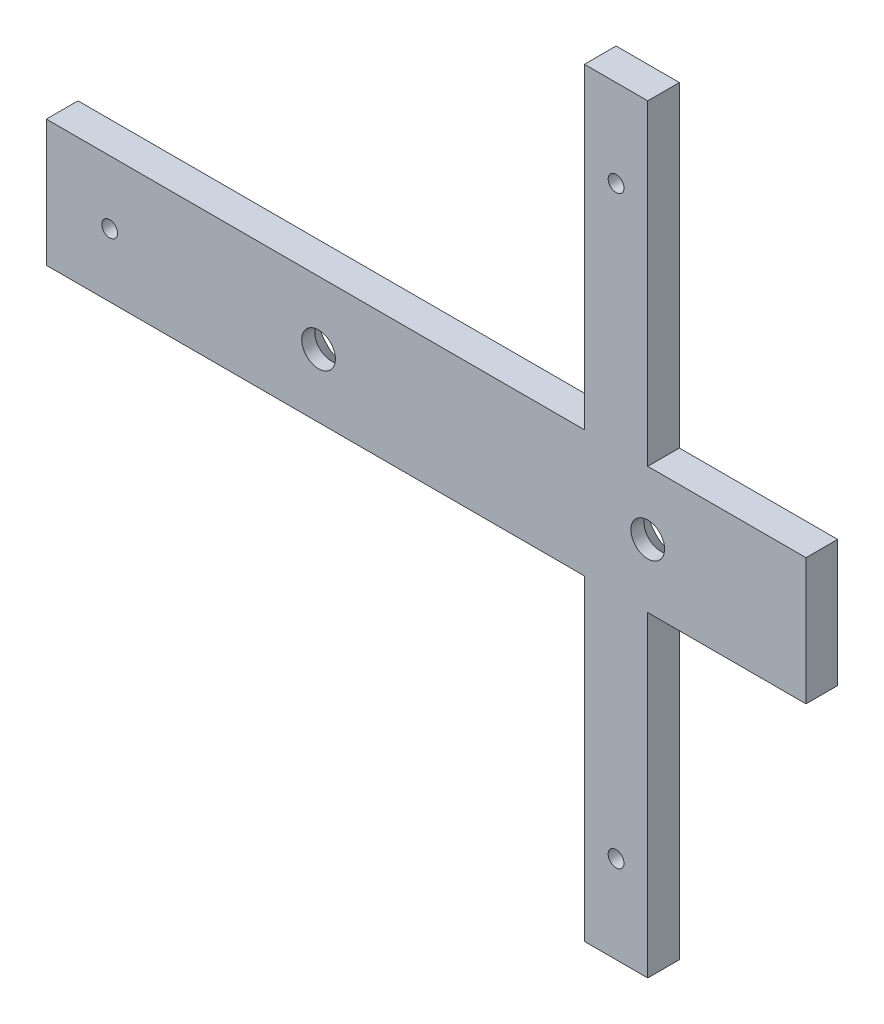
SolidWorks part; units mm, degrees
material "Brass"
ref_plane "Front Plane" through (0, 0, 0) normal (0, 0, 1) x (1, 0, 0)
ref_plane "Top Plane" through (0, 0, 0) normal (0, 1, 0) x (1, 0, 0)
ref_plane "Right Plane" through (0, 0, 0) normal (1, 0, 0) x (0, 0, -1)
sketch "Sketch1" plane through (0, 0, 0) normal (0, 0, 1) x (1, 0, 0)
  line L0 (-76.2, 76.2) -> (76.2, -76.2) construction
  line L1 (-76.2, 76.2) -> (76.2, 76.2)
  line L2 (-76.2, 76.2) -> (-76.2, -76.2)
  line L3 (-76.2, -76.2) -> (76.2, -76.2)
  line L4 (76.2, 76.2) -> (76.2, -76.2)
  dimension "D1" = 152.4
  dimension "D2" = 152.4
extrude "Extrude1" add sketch "Sketch1" along normal blind 6.35
sketch "Sketch2" plane through (0, 0, 6.35) normal (0, 0, 1) x (1, 0, 0)
  line L0 (0, -1000) -> (0, 49000) construction
  line L1 (-1000, 0) -> (49000, 0) construction
  line L2 (-132.7586, -39.9865) -> (29.8222, 53.8796) construction
  line L3 (-974.9255, 526.2118) -> (42254.3563, -24432.2257) construction
  circle A0 centre (-63.5, 0) radius 1.5875
  circle A3 centre (38.1, 58.6588) radius 1.5875
  circle A4 centre (38.1, -58.6588) radius 1.5875
  dimension "D4" = 3.175
  dimension "D5" = 3.175
  dimension "D6" = 3.175
  dimension "D9" = 101.6
extrude "Extrude2" cut sketch "Sketch2" against normal through all
sketch "Sketch3" plane through (0, 0, 6.35) normal (0, 0, 1) x (1, 0, 0)
  line L0 (-76.2, 12.7) -> (31.75, 12.7)
  line L1 (-76.2, 76.2) -> (-76.2, -76.2) construction
  line L2 (31.75, 12.7) -> (31.75, 76.2)
  line L3 (76.2, 76.2) -> (-76.2, 76.2) construction
  line L4 (31.75, 76.2) -> (44.45, 76.2)
  line L5 (44.45, 76.2) -> (44.45, 12.7)
  line L6 (44.45, 12.7) -> (76.2, 12.7)
  line L7 (76.2, -76.2) -> (76.2, 76.2) construction
  line L8 (76.2, 12.7) -> (76.2, -12.7)
  line L9 (76.2, -12.7) -> (44.45, -12.7)
  line L10 (44.45, -12.7) -> (44.45, -76.2)
  line L11 (-76.2, -76.2) -> (76.2, -76.2) construction
  line L12 (44.45, -76.2) -> (31.75, -76.2)
  line L13 (31.75, -76.2) -> (31.75, -12.7)
  line L14 (31.75, -12.7) -> (-76.2, -12.7)
  line L15 (-76.2, -12.7) -> (-76.2, 12.7)
  line L16 (-1000, 0) -> (49000, 0) construction
  line L17 (38.1, -1059.479) -> (38.1, 48940.521) construction
  dimension "D1" = 12.7
  dimension "D2" = 12.7
  dimension "D3" = 6.35
  dimension "D4" = 6.35
  dimension "D5" = 12.7
  dimension "D6" = 12.7
  dimension "D7" = 6.35
extrude "Extrude3" cut sketch "Sketch3" against normal through all flip side to cut
hole_wizard "CSK for 1/4 Flat Head Socket Cap Screw1" positions "Sketch4" profile "Sketch5" countersink size "1/4" standard "Ansi Inch" end condition through all
sketch "Sketch4" plane through (21.5209, 5.3613, 0) normal (0, 0, -1) x (1, 0, 0)
  point P0 (-43.1109, 5.3613)
sketch "Sketch5" plane through (-21.59, 0, 0) normal (1, 0, 0) x (0, 1, 0)
  line L0 (0, 0) -> (0, 6.35)
  line L1 (0, 6.35) -> (3.3782, 6.35)
  line L2 (3.3782, 6.35) -> (3.3782, 3.7284)
  line L3 (3.3782, 3.7284) -> (6.6192, 0)
  line L4 (6.6192, 0) -> (0, 0)
  line L5 (-3.3782, 3.7284) -> (-6.6192, 0) construction
  line L6 (0, -6.35) -> (0, 107.95) construction
  dimension "Thru Hole Dia." = 6.7564
  dimension "Thru Hole Depth" = 6.35
  dimension "Near C'Sink Dia." = 13.2385
  dimension "Near C'Sink Angle" = 82
hole_wizard "CSK for 1/4 Flat Head Socket Cap Screw2" positions "Sketch6" profile "Sketch7" countersink size "1/4" standard "Ansi Inch" end condition through all
sketch "Sketch6" plane through (21.5209, 5.3613, 0) normal (0, 0, -1) x (1, 0, 0)
  point P0 (22.9291, 5.3613)
sketch "Sketch7" plane through (44.45, 0, 0) normal (1, 0, 0) x (0, 1, 0)
  line L0 (0, 0) -> (0, 6.35)
  line L1 (0, 6.35) -> (3.3782, 6.35)
  line L2 (3.3782, 6.35) -> (3.3782, 3.7284)
  line L3 (3.3782, 3.7284) -> (6.6192, 0)
  line L4 (6.6192, 0) -> (0, 0)
  line L5 (-3.3782, 3.7284) -> (-6.6192, 0) construction
  line L6 (0, -6.35) -> (0, 107.95) construction
  dimension "Thru Hole Dia." = 6.7564
  dimension "Thru Hole Depth" = 6.35
  dimension "Near C'Sink Dia." = 13.2385
  dimension "Near C'Sink Angle" = 82
